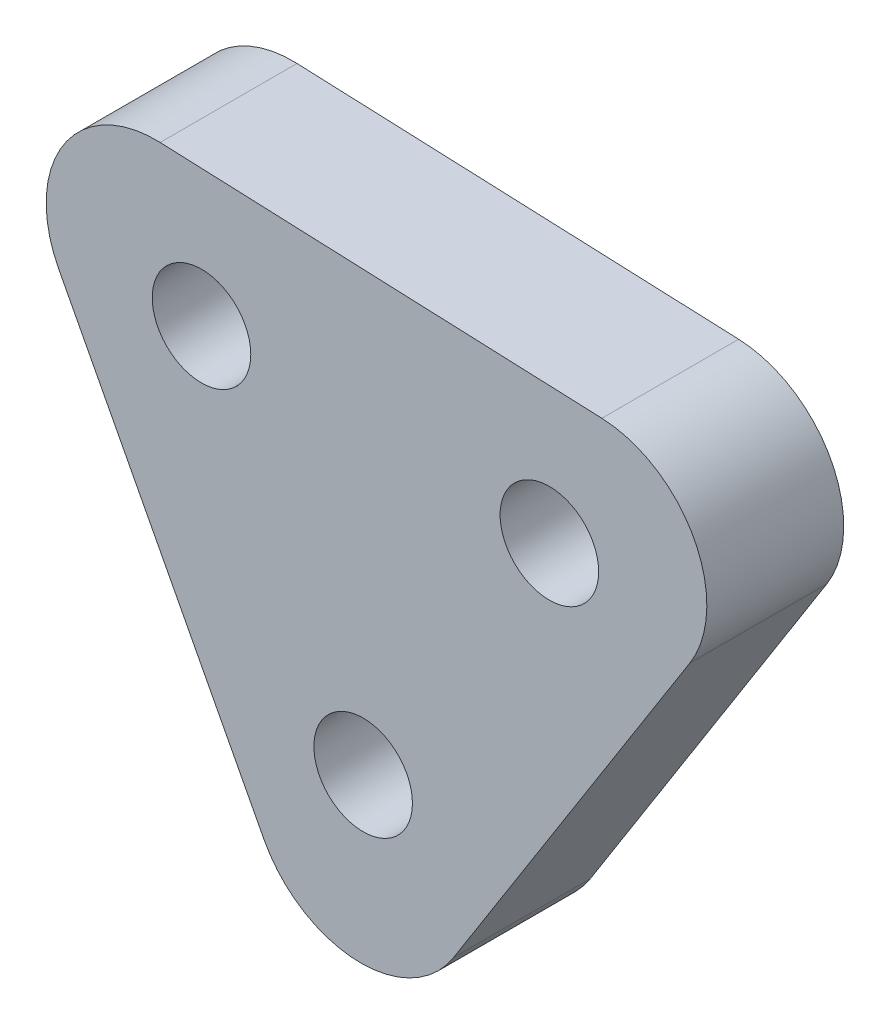
SolidWorks part; units mm, degrees
ref_plane "Plan de face" through (0, 0, 0) normal (0, 0, 1) x (1, 0, 0)
ref_plane "Plan de dessus" through (0, 0, 0) normal (0, 1, 0) x (1, 0, 0)
ref_plane "Plan de droite" through (0, 0, 0) normal (1, 0, 0) x (0, 0, -1)
sketch "Esquisse1" plane through (0, 0, 0) normal (0, 0, 1) x (1, 0, 0)
  line L0 (-17.1206, 28.5377) -> (-19.2016, -22.5007) construction
  line L1 (-62.67, -20.3147) -> (0.6424, 12.876) construction
  line L2 (-57.2742, 27.778) -> (-8.8082, -2.9021) construction
  line L3 (-32.7994, 12.2808) -> (-2.8174, 11.0584)
  line L4 (-2.8174, 11.0584) -> (-18.8667, -14.2876)
  line L5 (-18.8667, -14.2876) -> (-32.7994, 12.2808)
  circle A0 centre (-18.4595, -4.301) radius 1.8
  circle A1 centre (-24.3654, 6.946) radius 1.8
  circle A2 centre (-11.6576, 6.4279) radius 1.8
  circle A3 centre (-11.6576, 6.4279) radius 2 construction
  circle A4 centre (-24.3654, 6.946) radius 2 construction
  point P6 (-18.1611, 3.0185)
  point P9 (-10.842, -1.6146)
  point P18 (-34.9973, 9.986)
  point P20 (-25.833, -1.0034)
  point P28 (-17.8084, 11.6696)
  dimension "D1" = 120
  dimension "D2" = 120
extrude "Boss.-Extru.1" add sketch "Esquisse1" along normal blind 5
fillet "Congé1" radius 4 3 edges at (-18.8667, -14.2876, 2.5) (-32.7994, 12.2808, 2.5) (-2.8174, 11.0584, 2.5)
